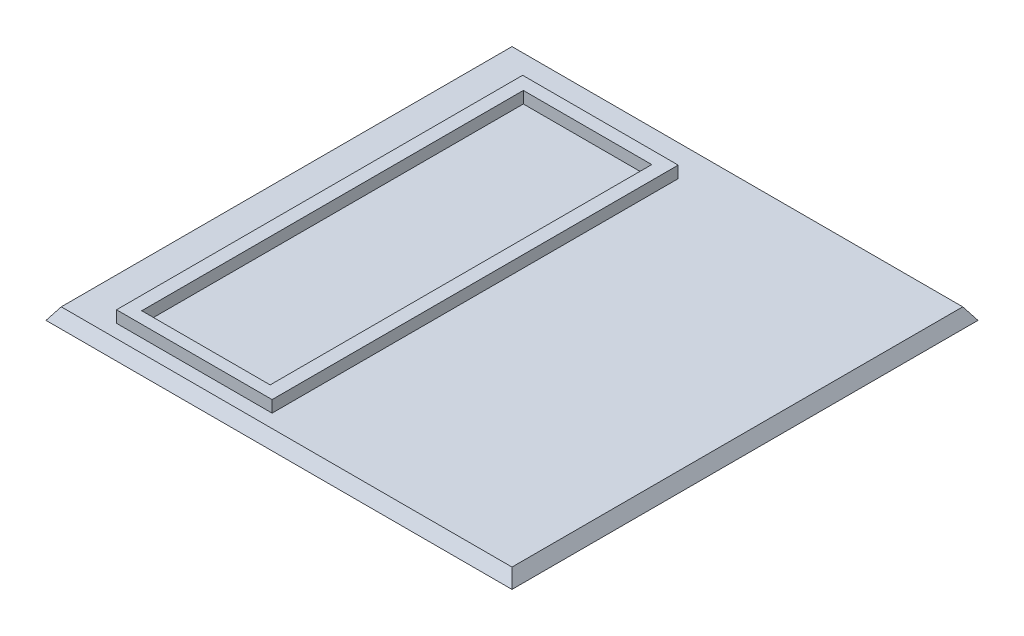
SolidWorks part; units mm, degrees
ref_plane "Front Plane" through (0, 0, 0) normal (0, 0, 1) x (1, 0, 0)
ref_plane "Top Plane" through (0, 0, 0) normal (0, 1, 0) x (1, 0, 0)
ref_plane "Right Plane" through (0, 0, 0) normal (1, 0, 0) x (0, 0, -1)
sketch "Sketch1" plane through (0, 0, 0) normal (0, 1, 0) x (1, 0, 0)
  line L1 (-45.5658, 132.4375) -> (156.0467, 132.4375)
  line L2 (-45.5658, 132.4375) -> (-45.5658, -69.175)
  line L3 (-45.5658, -69.175) -> (156.0467, -69.175)
  line L4 (156.0467, 132.4375) -> (156.0467, -69.175)
extrude "Boss-Extrude1" add sketch "Sketch1" along normal blind 5.08 draft 33
sketch "Sketch2" plane through (0, 5.08, 0) normal (0, 1, 0) x (1, 0, 0)
  line L1 (-18.3058, 110.0803) -> (37.2567, 110.0803)
  line L2 (-18.3058, 110.0803) -> (-18.3058, -55.0197)
  line L3 (-18.3058, -55.0197) -> (37.2567, -55.0197)
  line L4 (37.2567, 110.0803) -> (37.2567, -55.0197)
  line L10 (-24.13, 115.6077) -> (43.18, 115.6077)
  line L11 (-24.13, 115.6077) -> (-24.13, 110.0803)
  line L12 (-24.13, 110.0803) -> (43.18, 110.0803)
  line L13 (43.18, 115.6077) -> (43.18, 110.0803)
  line L14 (43.18, 110.0803) -> (37.2567, 110.0803)
  line L15 (43.18, 110.0803) -> (43.18, -55.0197)
  line L16 (43.18, -55.0197) -> (37.2567, -55.0197)
  line L17 (37.2567, 110.0803) -> (37.2567, -55.0197)
  line L18 (-24.13, 110.0803) -> (-18.3058, 110.0803)
  line L19 (-24.13, 110.0803) -> (-24.13, -55.0197)
  line L20 (-24.13, -55.0197) -> (-18.3058, -55.0197)
  line L21 (-18.3058, 110.0803) -> (-18.3058, -55.0197)
  line L22 (-24.13, -55.0197) -> (43.18, -55.0197)
  line L23 (-24.13, -55.0197) -> (-24.13, -60.1011)
  line L24 (-24.13, -60.1011) -> (43.18, -60.1011)
  line L25 (43.18, -55.0197) -> (43.18, -60.1011)
  point P16 (0, 0)
  point P17 (0, 0)
  dimension "D1" = 165.1
  dimension "D2" = 67.31
extrude "Boss-Extrude3" add sketch "Sketch2" along normal blind 5.08 contours L13 L10 L11 L12 L1 | L16 L15 L12 L4 | L25 L16 L3 L20 L23 L24
